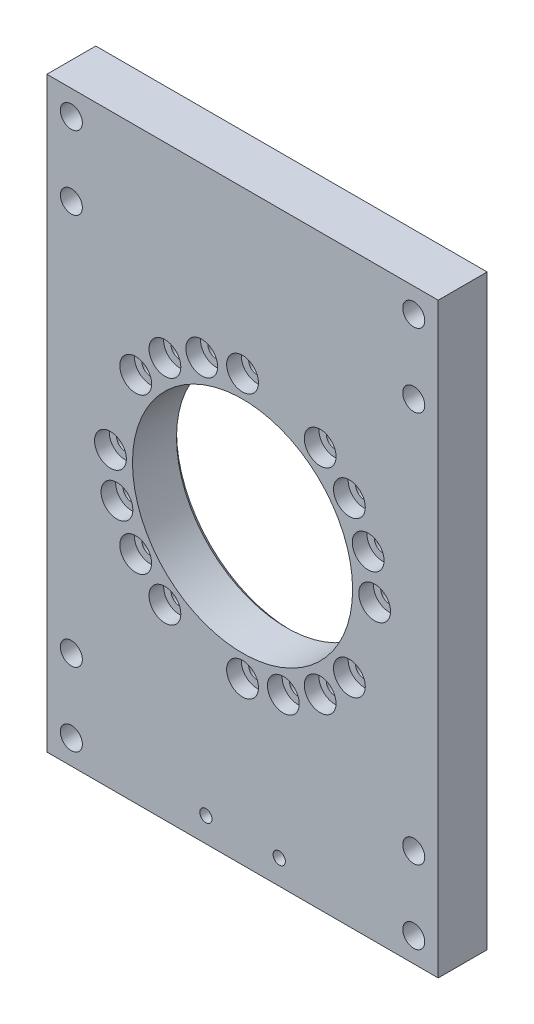
SolidWorks part; units mm, degrees
material "ALUMINIUM,  6082-T6"
ref_plane "Front Plane" through (0, 0, 0) normal (0, 0, 1) x (1, 0, 0)
ref_plane "Top Plane" through (0, 0, 0) normal (0, 1, 0) x (1, 0, 0)
ref_plane "Right Plane" through (0, 0, 0) normal (1, 0, 0) x (0, 0, -1)
sketch "Sketch1" plane through (0, 0, 0) normal (0, 0, 1) x (1, 0, 0)
  line L0 (40, 60) -> (-40, -60) construction
  line L1 (-40, 60) -> (40, 60)
  line L2 (-40, 60) -> (-40, -60)
  line L3 (-40, -60) -> (40, -60)
  line L4 (40, 60) -> (40, -60)
  circle A0 centre (0, 0) radius 22.5
  dimension "D1" = 45
  dimension "D2" = 80
  dimension "D3" = 120
extrude "Boss-Extrude1" add sketch "Sketch1" along normal blind 10
hole_wizard "CBORE for M3 Hex Socket Head Cap Screw1" positions "Sketch11" profile "Sketch3" counterbore size "M3" standard "ISO" end condition through all
sketch "Sketch11" plane through (0, 0, 10) normal (0, 0, 1) x (1, 0, 0)
  line L47 (-27, 0) -> (27, 0) construction
  line L52 (0, 27) -> (0, -27) construction
  line L54 (-25.6785, -8.3435) -> (25.6785, 8.3435) construction
  line L57 (21.8435, 15.8702) -> (-21.8435, -15.8702) construction
  line L60 (-15.8702, -21.8435) -> (15.8702, 21.8435) construction
  line L62 (-8.3435, 25.6785) -> (8.3435, -25.6785) construction
  line L65 (-15.8702, 21.8435) -> (15.8702, -21.8435) construction
  line L68 (-21.8435, 15.8702) -> (21.8435, -15.8702) construction
  circle A2 centre (0, 0) radius 27 construction
  circle A3 centre (0, 0) radius 22.5 construction
  point P157 (-27, 0)
  point P164 (-25.6785, -8.3435)
  point P166 (-21.8435, -15.8702)
  point P168 (-15.8702, -21.8435)
  point P170 (27, 0)
  point P172 (25.6785, 8.3435)
  point P174 (21.8435, 15.8702)
  point P176 (15.8702, 21.8435)
  point P178 (0, 27)
  point P180 (-8.3435, 25.6785)
  point P184 (-15.8702, 21.8435)
  point P186 (-21.8435, 15.8702)
  point P188 (0, -27)
  point P190 (8.3435, -25.6785)
  point P192 (15.8702, -21.8435)
  point P194 (21.8435, -15.8702)
  dimension "D1" = 54
  dimension "D2" = 18
  dimension "D3" = 18
  dimension "D4" = 18
  dimension "D5" = 18
  dimension "D6" = 18
  dimension "D7" = 18
sketch "Sketch3" plane through (-27, 0, 10) normal (1, 0, 0) x (0, -1, 0)
  line L0 (0, 0) -> (0, 10)
  line L1 (0, 10) -> (1.75, 10)
  line L3 (1.75, 10) -> (1.75, 3)
  line L4 (1.75, 3) -> (3.25, 3)
  line L5 (3.25, 3) -> (3.25, 0)
  line L7 (3.25, 0) -> (0, 0)
  line L11 (0, -6.35) -> (0, 107.95) construction
  dimension "Thru Hole Dia." = 3.5
  dimension "Thru Hole Depth" = 10
  dimension "C'Bore Dia." = 6.5
  dimension "C'Bore Depth" = 3
chamfer "Chamfer1" distance 1 angle 45 1 edges at (22.5, 0, 0)
hole_wizard "Ø4.5 (4.5) Diameter Hole1" positions "Sketch7" profile "Sketch8" hole size "Ø4.5" standard "ISO" end condition through all
sketch "Sketch7" plane through (0, 0, 10) normal (0, 0, 1) x (1, 0, 0)
  line L1 (-35, 55) -> (-35, -55) construction
  line L3 (-35, -55) -> (35, -55) construction
  line L5 (35, -55) -> (35, 55) construction
  line L7 (35, 55) -> (-35, 55) construction
  line L15 (-35, 55) -> (35, -55) construction
  line L17 (40, 60) -> (-40, 60) construction
  line L18 (-35, -40) -> (35, -40) construction
  line L21 (35, 40) -> (-35, 40) construction
  line L23 (-35, -40) -> (35, 40) construction
  line L24 (-40, 60) -> (-40, -60) construction
  point P0 (-35, 55)
  point P4 (35, 55)
  point P10 (35, -55)
  point P14 (-35, -55)
  point P71 (-35, -40)
  point P74 (-35, 40)
  point P77 (35, 40)
  point P80 (35, -40)
  dimension "D1" = 15
  dimension "D2" = 5
  dimension "D3" = 5
sketch "Sketch8" plane through (-35, 55, 10) normal (1, 0, 0) x (0, -1, 0)
  line L0 (0, 0) -> (0, 10)
  line L1 (0, 10) -> (2.25, 10)
  line L2 (2.25, 10) -> (2.25, 0)
  line L5 (2.25, 0) -> (0, 0)
  line L11 (0, -6.35) -> (0, 107.95) construction
  dimension "Thru Hole Dia." = 4.5
  dimension "Thru Hole Depth" = 10
hole_wizard "M3 Tapped Hole1" positions "Sketch9" profile "Sketch10" tap size "M3" standard "ISO" end condition through all
sketch "Sketch9" plane through (0, 0, 0) normal (0, 0, -1) x (-1, 0, 0)
  line L0 (-7.5, -55) -> (7.5, -55) construction
  line L5 (0, 0) -> (0, -55) construction
  line L7 (40, -60) -> (-40, -60) construction
  point P0 (-7.5, -55)
  point P2 (7.5, -55)
  dimension "D1" = 15
  dimension "D2" = 5
cosmetic thread "Hole Thread1" parameters "D2"=3
cosmetic thread "Hole Thread2" parameters "D2"=3
sketch "Sketch10" plane through (7.5, -55, 0) normal (1, 0, 0) x (0, 1, 0)
  line L0 (0, 0) -> (0, 10)
  line L1 (0, 10) -> (1.25, 10)
  line L2 (1.25, 10) -> (1.25, 0)
  line L5 (1.25, 0) -> (0, 0)
  line L11 (0, -6.35) -> (0, 107.95) construction
  dimension "Thru Tap Drill Dia." = 2.5
  dimension "Thru Tap Drill Depth" = 10
